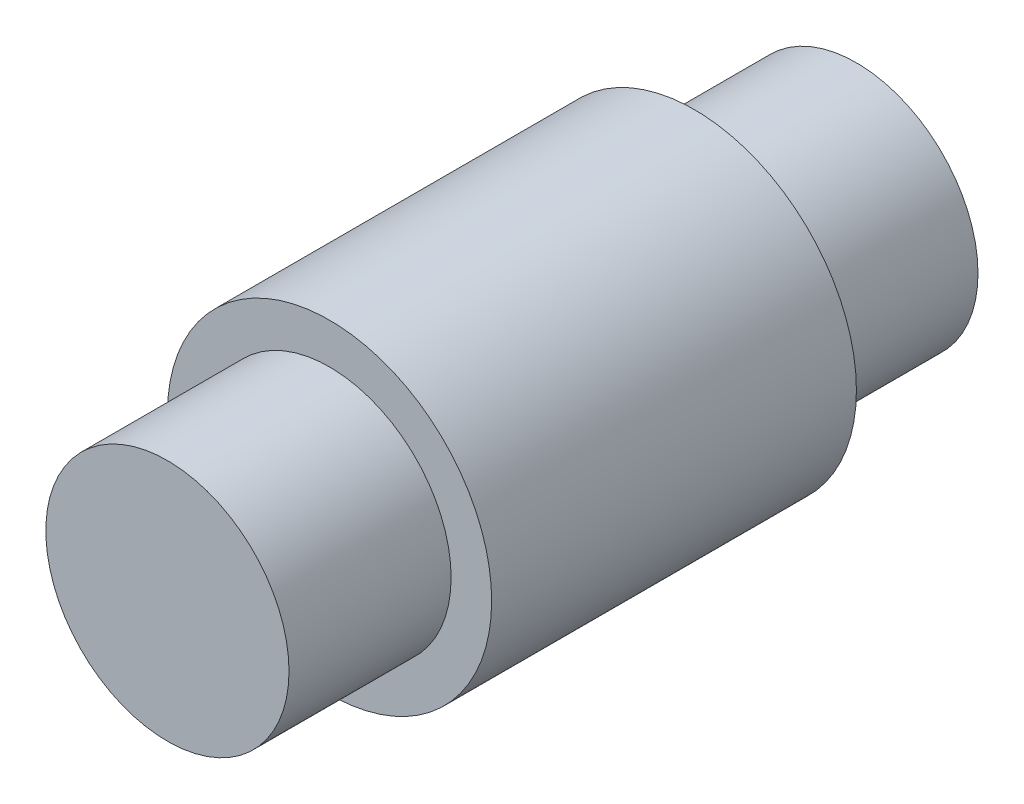
SolidWorks part; units mm, degrees
ref_plane "Plan de face" through (0, 0, 0) normal (0, 0, 1) x (1, 0, 0)
ref_plane "Plan de dessus" through (0, 0, 0) normal (0, 1, 0) x (1, 0, 0)
ref_plane "Plan de droite" through (0, 0, 0) normal (1, 0, 0) x (0, 0, -1)
sketch "Esquisse2" plane through (0, 0, 0) normal (0, 0, 1) x (1, 0, 0)
  circle A0 centre (0, 0) radius 2
  dimension "D1" = 4
extrude "Boss.-Extru.1" add sketch "Esquisse2" along normal blind 2.25
sketch "Esquisse3" plane through (0, 0, 2.25) normal (0, 0, 1) x (1, 0, 0)
  circle A0 centre (0, 0) radius 1.5
  dimension "D1" = 3
extrude "Boss.-Extru.2" add sketch "Esquisse3" along normal blind 2
mirror "Symétrie1" about plane through (0, 0, 0) normal (0, 0, 1) of "Boss.-Extru.2", "Boss.-Extru.1"
